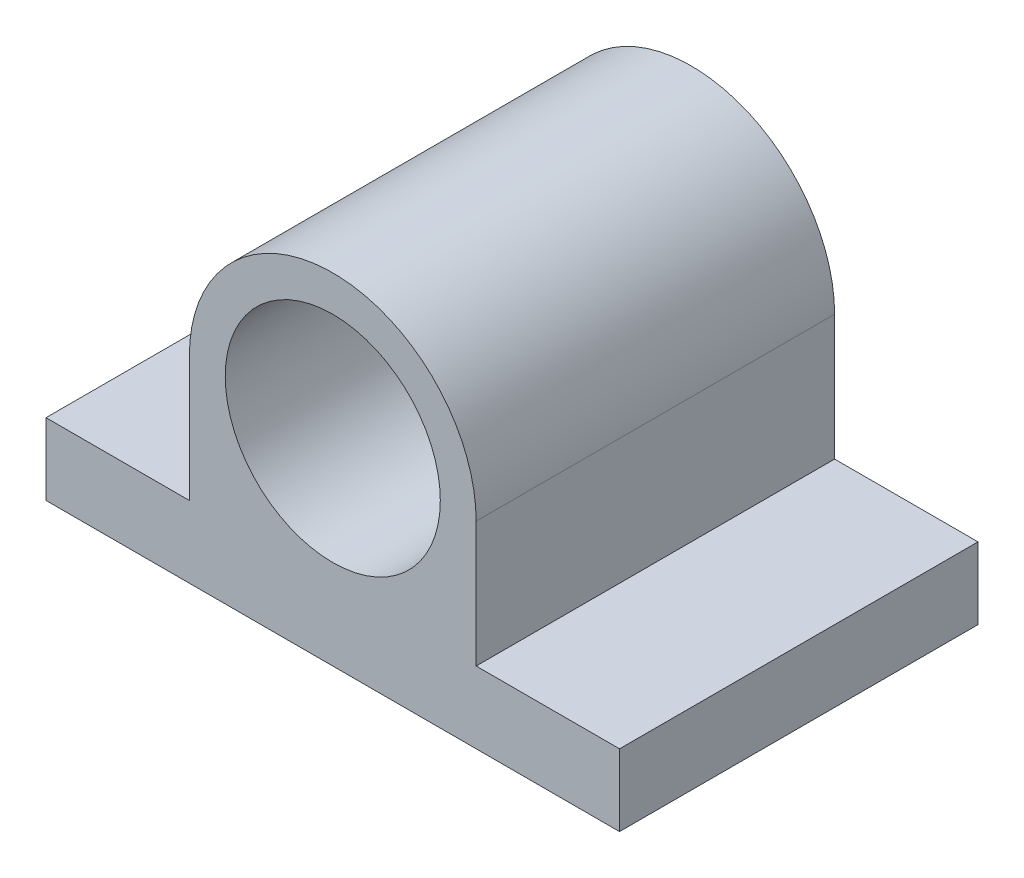
SolidWorks part; units mm, degrees
ref_plane "Front Plane" through (0, 0, 0) normal (0, 0, 1) x (1, 0, 0)
ref_plane "Top Plane" through (0, 0, 0) normal (0, 1, 0) x (1, 0, 0)
ref_plane "Right Plane" through (0, 0, 0) normal (1, 0, 0) x (0, 0, -1)
sketch "Sketch1" plane through (0, 0, 0) normal (0, 0, 1) x (1, 0, 0)
  line L1 (0, 0) -> (80, 0)
  line L2 (0, 0) -> (0, 10)
  line L3 (0, 10) -> (20, 10)
  line L4 (80, 0) -> (80, 10)
  line L11 (60, 10) -> (80, 10)
  line L13 (60, 10) -> (60, 27.5)
  line L14 (20, 10) -> (20, 27.5)
  arc A0 (60, 27.5) -> (20, 27.5) centre (40, 27.5) ccw
  circle A1 centre (40, 27.5) radius 15
  point P4 (40, 10)
extrude "Boss-Extrude1" add sketch "Sketch1" along normal blind 50
